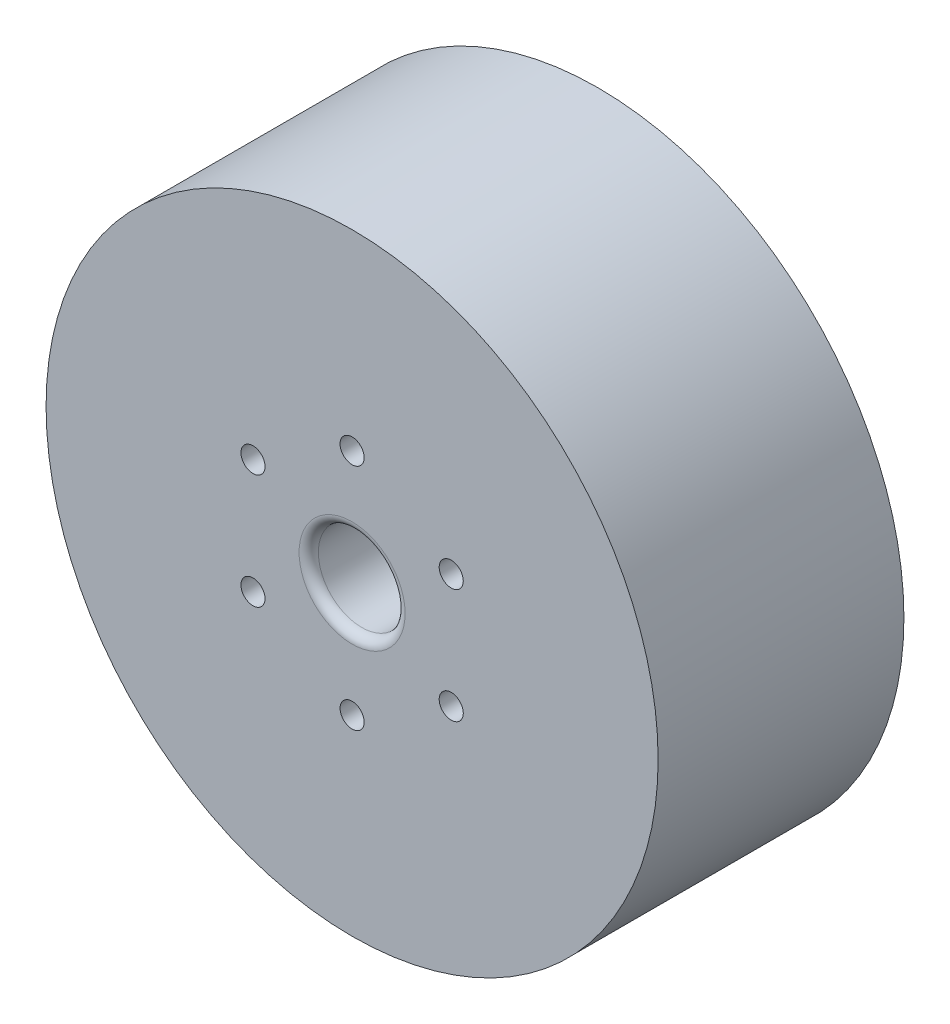
SolidWorks part; units mm, degrees
material "PUR"
ref_plane "Front Plane" through (0, 0, 0) normal (0, 0, 1) x (1, 0, 0)
ref_plane "Top Plane" through (0, 0, 0) normal (0, 1, 0) x (1, 0, 0)
ref_plane "Right Plane" through (0, 0, 0) normal (1, 0, 0) x (0, 0, -1)
sketch "Sketch1" plane through (0, 0, 0) normal (0, 0, 1) x (1, 0, 0)
  line L0 (0, 0) -> (0, 23.75) construction
  circle A0 centre (0, 0) radius 63.5
  circle A1 centre (0, 0) radius 9
  circle A2 centre (0, 0) radius 23.75 construction
  circle A3 centre (0, 23.75) radius 2.5
  circle A4 centre (20.5681, 11.875) radius 2.5
  circle A5 centre (20.5681, -11.875) radius 2.5
  circle A6 centre (0, -23.75) radius 2.5
  circle A7 centre (-20.5681, -11.875) radius 2.5
  circle A8 centre (-20.5681, 11.875) radius 2.5
  dimension "D1" = 127
  dimension "D2" = 18
  dimension "D3" = 47.5
  dimension "D4" = 5
  dimension "D6" = 23.75
  dimension "D5" = 6
extrude "Boss-Extrude1" add sketch "Sketch1" along normal mid plane 51
fillet "Fillet1" radius 2 2 edges at (9, 0, -25.5) (9, 0, 25.5)
